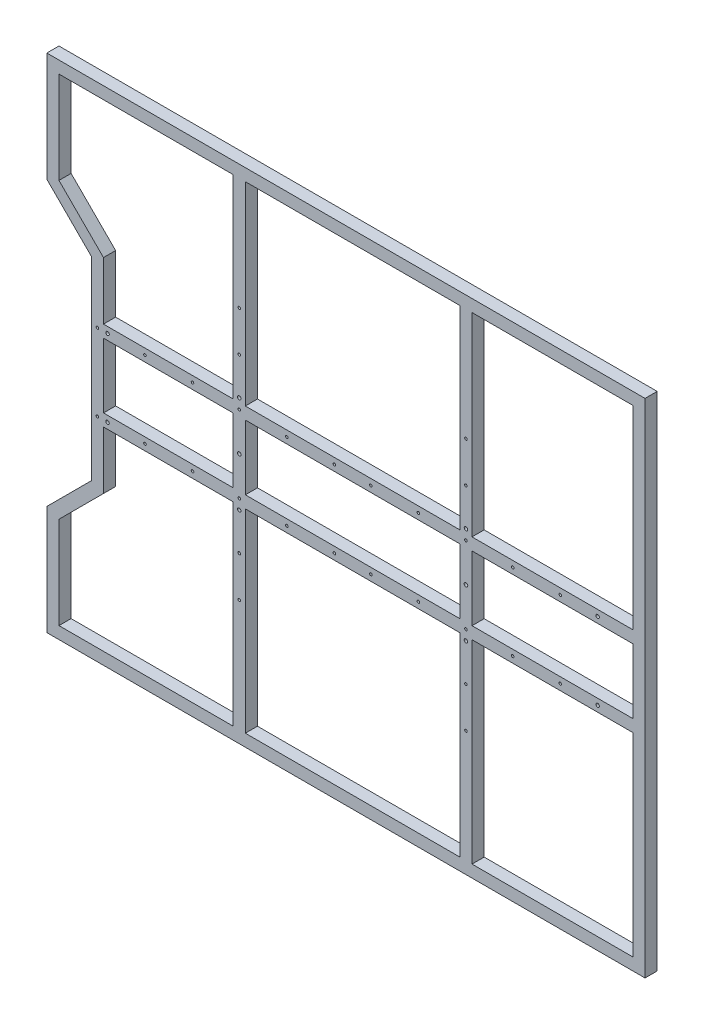
SolidWorks part; units mm, degrees
ref_plane "前视基准面" through (0, 0, 0) normal (0, 0, 1) x (1, 0, 0)
ref_plane "上视基准面" through (0, 0, 0) normal (0, 1, 0) x (1, 0, 0)
ref_plane "右视基准面" through (0, 0, 0) normal (1, 0, 0) x (0, 0, -1)
sketch "草图2" plane through (0, 0, 0) normal (0, 0, 1) x (1, 0, 0)
  line L0 (0, 0) -> (56.6289, 0) construction
  line L1 (-377.7002, 310) -> (361.2002, 310)
  line L2 (-377.7002, 310) -> (-377.7002, 295)
  line L3 (-362.7002, 295) -> (-147.5, 295)
  line L4 (361.2002, 310) -> (361.2002, 295)
  line L5 (-377.7002, 310) -> (-362.7002, 310)
  line L6 (-377.7002, 310) -> (-377.7002, 175)
  line L7 (-365.7002, 163) -> (-362.7002, 163)
  line L8 (-362.7002, 295) -> (-362.7002, 181.2132)
  line L9 (-365.7002, 163) -> (-362.7002, 163)
  line L10 (-377.7002, 175) -> (-377.7002, 176.5)
  line L17 (-307.7002, 40) -> (-147.5, 40)
  line L18 (-322.7002, 40) -> (-322.7002, 55)
  line L19 (-307.7002, 55) -> (-147.5, 55)
  line L20 (361.2002, 40) -> (361.2002, 55)
  line L22 (361.2002, 40) -> (361.2002, 310)
  line L23 (361.2002, 310) -> (346.2002, 310)
  line L24 (346.2002, 55) -> (346.2002, 295)
  line L26 (147.5, 55) -> (147.5, 295)
  line L27 (147.5, 310) -> (132.5, 310)
  line L28 (132.5, 55) -> (132.5, 295)
  line L30 (-132.5, 55) -> (-132.5, 295)
  line L31 (-132.5, 310) -> (-147.5, 310)
  line L32 (-147.5, 55) -> (-147.5, 295)
  line L33 (291.2002, 79.7641) -> (291.2002, 186.8682) construction
  line L34 (-362.7002, 181.2132) -> (-307.7002, 126.2132)
  line L35 (-307.7002, 126.2132) -> (-307.7002, 105)
  line L36 (-322.7002, 120) -> (-377.7002, 175)
  line L37 (-132.5, 55) -> (132.5, 55)
  line L38 (-322.7002, 120) -> (-322.7002, 40)
  line L39 (-307.7002, 126.2132) -> (-307.7002, 55)
  line L40 (-132.5, 295) -> (132.5, 295)
  line L41 (147.5, 295) -> (346.2002, 295)
  line L42 (147.5, 55) -> (346.2002, 55)
  line L43 (147.5, -55) -> (346.2002, -55)
  line L44 (147.5, -295) -> (346.2002, -295)
  line L45 (-132.5, -295) -> (132.5, -295)
  line L46 (-307.7002, -126.2132) -> (-307.7002, -55)
  line L47 (-322.7002, -120) -> (-322.7002, -40)
  line L48 (-132.5, -55) -> (132.5, -55)
  line L49 (-322.7002, -120) -> (-377.7002, -175)
  line L50 (-307.7002, -126.2132) -> (-307.7002, -105)
  line L51 (-362.7002, -181.2132) -> (-307.7002, -126.2132)
  line L52 (-147.5, -55) -> (-147.5, -295)
  line L53 (-132.5, -310) -> (-147.5, -310)
  line L54 (-132.5, -55) -> (-132.5, -295)
  line L56 (132.5, -55) -> (132.5, -295)
  line L57 (147.5, -310) -> (132.5, -310)
  line L58 (147.5, -55) -> (147.5, -295)
  line L59 (-132.5, -40) -> (132.5, -40)
  line L60 (346.2002, -55) -> (346.2002, -295)
  line L61 (361.2002, -310) -> (346.2002, -310)
  line L62 (361.2002, -40) -> (361.2002, -310)
  line L63 (147.5, 40) -> (346.2002, 40)
  line L64 (361.2002, -40) -> (361.2002, -55)
  line L65 (-307.7002, -55) -> (-147.5, -55)
  line L66 (-322.7002, -40) -> (-322.7002, -55)
  line L67 (-307.7002, -40) -> (-147.5, -40)
  line L68 (-377.7002, -175) -> (-377.7002, -176.5)
  line L69 (-365.7002, -163) -> (-362.7002, -163)
  line L70 (-362.7002, -295) -> (-362.7002, -181.2132)
  line L71 (-365.7002, -163) -> (-362.7002, -163)
  line L72 (-377.7002, -310) -> (-377.7002, -175)
  line L73 (-377.7002, -310) -> (-362.7002, -310)
  line L74 (361.2002, -310) -> (361.2002, -295)
  line L75 (-362.7002, -295) -> (-147.5, -295)
  line L76 (-377.7002, -310) -> (-377.7002, -295)
  line L77 (-377.7002, -310) -> (361.2002, -310)
  line L78 (147.5, -40) -> (346.2002, -40)
  line L80 (-322.7002, 40) -> (-322.7002, -40)
  line L82 (-307.7002, 40) -> (-307.7002, -40)
  line L84 (-147.5, 40) -> (-147.5, -40)
  line L86 (-132.5, 40) -> (-132.5, -40)
  line L88 (132.5, 40) -> (132.5, -40)
  line L90 (147.5, 40) -> (147.5, -40)
  line L92 (346.2002, 40) -> (346.2002, -40)
  line L94 (361.2002, 40) -> (361.2002, -40)
  line L95 (-132.5, 40) -> (132.5, 40)
  circle A0 centre (140, 60) radius 2.1 construction
  circle A1 centre (-140, 60) radius 2.1 construction
  circle A2 centre (-302.7002, 47.5) radius 2.15 construction
  dimension "D8" = 7.5
  dimension "D9" = 7.5
  dimension "D11" = 7.5
  dimension "D1" = 15
  dimension "D2" = 15
  dimension "D3" = 15
  dimension "D4" = 15
  dimension "D6" = 15
  dimension "D7" = 15
  dimension "D10" = 240
  dimension "D14" = 55
  dimension "D16" = 15
  dimension "D17" = 50
extrude "凸台-拉伸1" add sketch "草图2" along normal blind 15
sketch "草图3" plane through (0, 0, 15) normal (0, 0, 1) x (1, 0, 0)
  line L0 (-170, 60) -> (-110, 60) construction
  line L1 (40.1698, 0) -> (-40.1698, 0) construction
  line L2 (0, 0) -> (0, 60) construction
  line L3 (-140, 153.0178) -> (-140, -19.3646) construction
  line L4 (-315.2002, 47.5) -> (315.2002, 47.5) construction
  line L5 (-307.7002, 55) -> (-147.5, 55) construction
  line L6 (-322.7002, 120) -> (-322.7002, -120) construction
  line L7 (140, 153.0178) -> (140, -19.3646) construction
  line L8 (170, 60) -> (110, 60) construction
  circle A0 centre (-140, 60) radius 2.15
  circle A1 centre (-315.2002, 47.5) radius 1.6
  circle A2 centre (-256.4668, 47.5) radius 1.6
  circle A3 centre (-197.7368, 47.5) radius 1.6
  circle A4 centre (-140, 47.5) radius 1.6
  circle A6 centre (-140, 156.23) radius 1.6
  circle A7 centre (-140, 106.23) radius 1.6
  circle A8 centre (-81.27, 47.5) radius 1.6
  circle A9 centre (-22.54, 47.5) radius 1.6
  circle A10 centre (-140, 0) radius 2.2407
  circle A11 centre (-302.7002, 47.5) radius 2.15 construction
  circle A12 centre (-302.7002, 47.5) radius 2.15
  circle A13 centre (-302.7002, -47.5) radius 2.15
  circle A14 centre (-22.54, -47.5) radius 1.6
  circle A15 centre (-81.27, -47.5) radius 1.6
  circle A16 centre (-140, -106.23) radius 1.6
  circle A17 centre (-140, -156.23) radius 1.6
  circle A18 centre (-140, -47.5) radius 1.6
  circle A19 centre (-197.7368, -47.5) radius 1.6
  circle A20 centre (-256.4668, -47.5) radius 1.6
  circle A21 centre (-315.2002, -47.5) radius 1.6
  circle A22 centre (-140, -60) radius 2.15
  circle A23 centre (140, -60) radius 2.15
  circle A25 centre (256.4668, -47.5) radius 1.6
  circle A26 centre (197.7368, -47.5) radius 1.6
  circle A27 centre (140, -47.5) radius 1.6
  circle A28 centre (140, -156.23) radius 1.6
  circle A29 centre (140, -106.23) radius 1.6
  circle A30 centre (81.27, -47.5) radius 1.6
  circle A31 centre (22.54, -47.5) radius 1.6
  circle A32 centre (302.7002, -47.5) radius 2.15
  circle A33 centre (302.7002, 47.5) radius 2.15
  circle A34 centre (140, 0) radius 2.2407
  circle A35 centre (22.54, 47.5) radius 1.6
  circle A36 centre (81.27, 47.5) radius 1.6
  circle A37 centre (140, 106.23) radius 1.6
  circle A38 centre (140, 156.23) radius 1.6
  circle A39 centre (140, 47.5) radius 1.6
  circle A40 centre (197.7368, 47.5) radius 1.6
  circle A41 centre (256.4668, 47.5) radius 1.6
  circle A43 centre (140, 60) radius 2.15
  spline S0 degree 3 poles (38.5704, -1.8021) (40.3626, -0.0123) (41.8126, 2.1192) (42.8191, 4.4435) (42.8191, 4.4436) knots -0.000022 -0.000022 -0.000022 -0.000022 0.999972 0.999994 0.999994 0.999994 0.999994 weights 1 1 1 1 1 construction
  point P34 (0, 0)
  point P41 (-140, 0)
  point P63 (0, 47.5)
  dimension "D1" = 4.3
  dimension "D10" = 3.2
  dimension "D2" = 7.5
  dimension "D3" = 7.5
  dimension "D4" = 58.7333
  dimension "D5" = 58.73
  dimension "D6" = 58.73
  dimension "D7" = 50
  dimension "D8" = 58.73
  dimension "D9" = 58.73
extrude "切除-拉伸1" cut sketch "草图3" against normal blind 15
